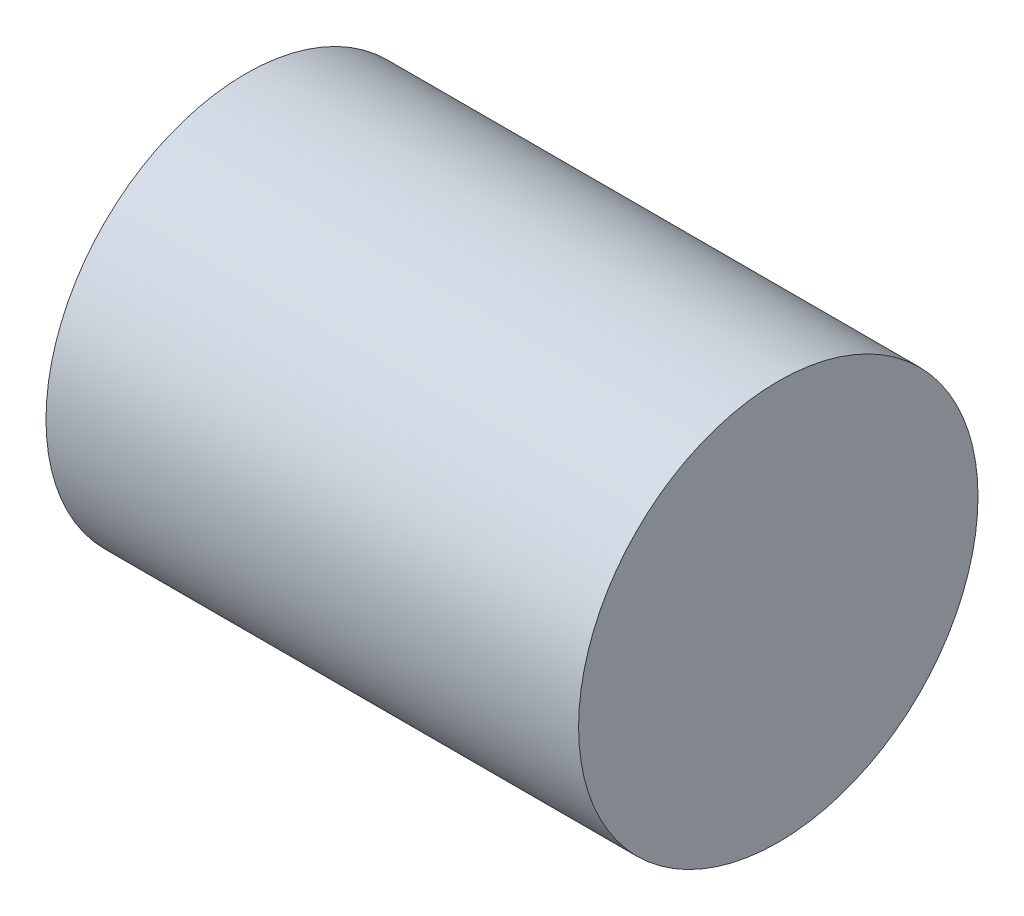
SolidWorks part; units mm, degrees
material "Abzugskoerper"
ref_plane "Ebene vorne" through (0, 0, 0) normal (0, 0, 1) x (1, 0, 0)
ref_plane "Ebene oben" through (0, 0, 0) normal (0, 1, 0) x (1, 0, 0)
ref_plane "Ebene rechts" through (0, 0, 0) normal (1, 0, 0) x (0, 0, -1)
sketch "Skizze1" plane through (0, 0, 0) normal (1, 0, 0) x (0, 0, -1)
  circle A0 centre (0, 0) radius 4.5
  dimension "d2" = 9
extrude "Aufsatz-Linear austragen1" add sketch "Skizze1" against normal blind 12
